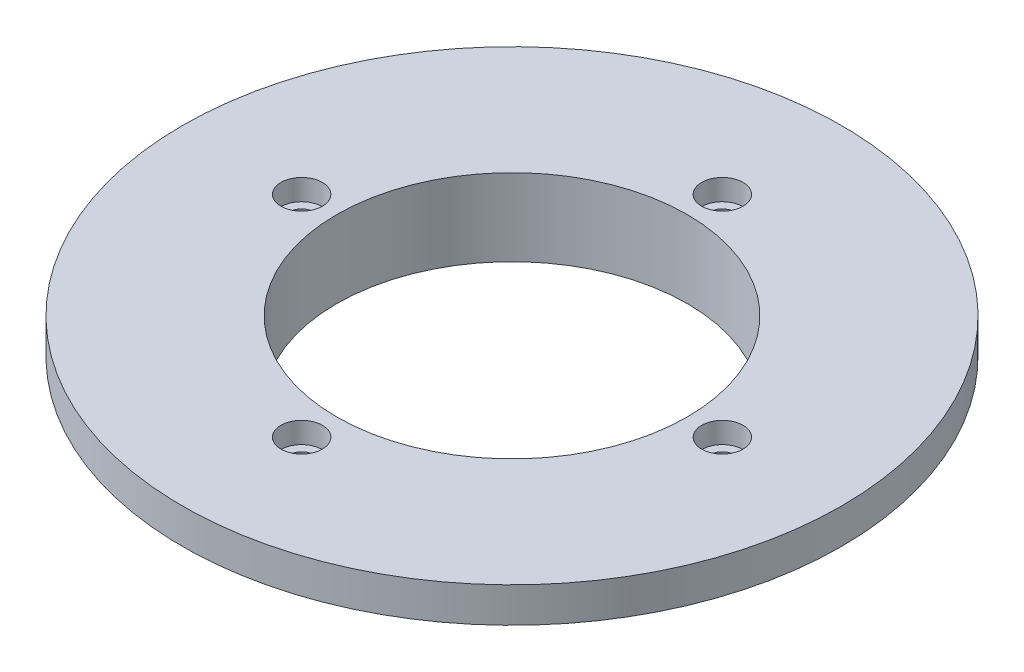
SolidWorks part; units mm, degrees
ref_plane "Front Plane" through (0, 0, 0) normal (0, 0, 1) x (1, 0, 0)
ref_plane "Top Plane" through (0, 0, 0) normal (0, 1, 0) x (1, 0, 0)
ref_plane "Right Plane" through (0, 0, 0) normal (1, 0, 0) x (0, 0, -1)
sketch "Sketch1" plane through (0, 0, 0) normal (0, 0, 1) x (1, 0, 0)
  line L0 (0, -62.2558) -> (0, 62.2558) construction
  line L1 (25, 0) -> (47, 0)
  line L2 (47, 0) -> (47, -5)
  line L3 (47, -5) -> (35, -5)
  line L4 (35, -5) -> (35, -11)
  line L5 (35, -11) -> (25, -11)
  line L6 (25, -11) -> (25, 0)
  point P3 (0, 0)
  dimension "D1" = 25
  dimension "D2" = 35
  dimension "D3" = 47
  dimension "D4" = 6
  dimension "D5" = 5
revolve "Revolve1" add sketch "Sketch1" angle 360 about L0
sketch "Sketch3" plane through (0, 0, 0) normal (0, 1, 0) x (1, 0, 0)
  circle A0 centre (0, 30) radius 1.7
  dimension "D1" = 3.4
  dimension "D2" = 30
extrude "Cut-Extrude1" cut sketch "Sketch3" against normal through all and the other way through all
pattern_circular "CirPattern1" count 4 over 360 about axis through (0, 0, 0) along (0, 1, 0) of "Cut-Extrude1"
sketch "Sketch4" plane through (0, 0, 0) normal (0, 1, 0) x (1, 0, 0)
  circle A0 centre (0, 30) radius 2.95
  dimension "D1" = 5.9
extrude "Cut-Extrude2" cut sketch "Sketch4" against normal blind 3
pattern_circular "CirPattern2" count 4 over 360 about axis through (0, 0, 0) along (0, 1, 0) of "Cut-Extrude2"
